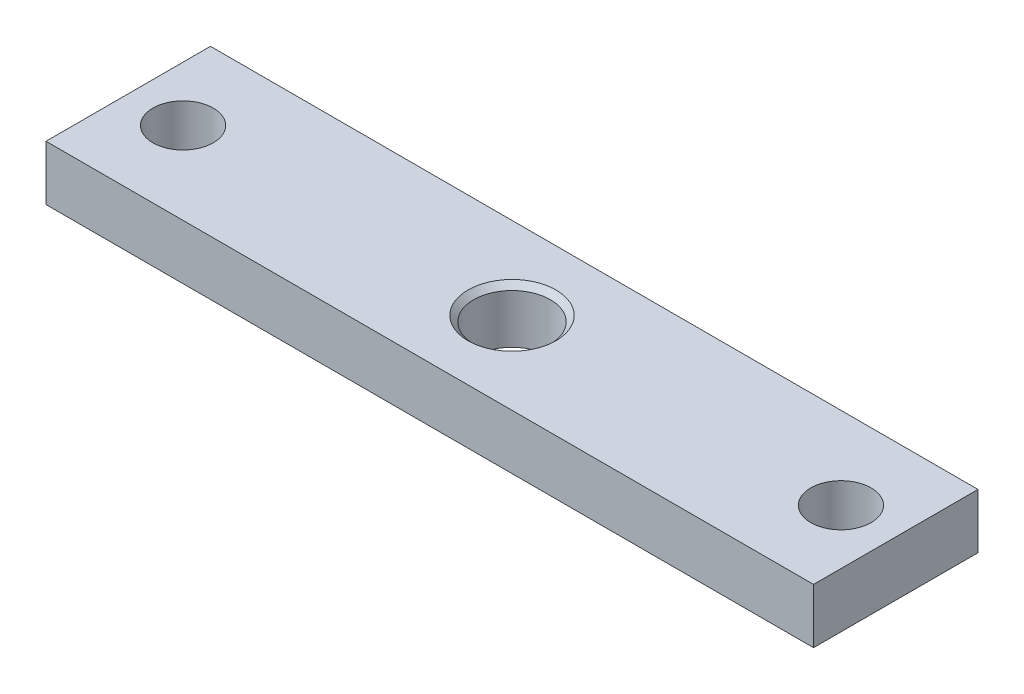
SolidWorks part; units mm, degrees
ref_plane "Front Plane" through (0, 0, 0) normal (0, 0, 1) x (1, 0, 0)
ref_plane "Top Plane" through (0, 0, 0) normal (0, 1, 0) x (1, 0, 0)
ref_plane "Right Plane" through (0, 0, 0) normal (1, 0, 0) x (0, 0, -1)
sketch "Sketch4" plane through (0, 0, 0) normal (0, 1, 0) x (1, 0, 0)
  line L1 (-70, 15) -> (70, 15)
  line L2 (-70, 15) -> (-70, -15)
  line L3 (-70, -15) -> (70, -15)
  line L4 (70, 15) -> (70, -15)
  line L5 (-70, 15) -> (70, -15) construction
  line L6 (-70, -15) -> (70, 15) construction
  point P0 (0, 0)
  dimension "D1" = 140
  dimension "D2" = 30
extrude "Boss-Extrude2" add sketch "Sketch4" along normal mid plane 10
sketch "Sketch5" plane through (0, 5, 0) normal (0, 1, 0) x (1, 0, 0)
  line L0 (-5.5, 0) -> (5.5, 0) construction
  circle A0 centre (-60, 0) radius 5.5
  circle A1 centre (60, 0) radius 5.5
  dimension "D1" = 11
  dimension "D2" = 60
  dimension "D3" = 120
extrude "Cut-Extrude1" cut sketch "Sketch5" against normal blind 63
sketch "Sketch6" plane through (0, 5, 0) normal (0, 1, 0) x (1, 0, 0)
  point P0 (0, 0)
hole_wizard "M16 Tapped Hole1" positions "3DSketch2" profile "Sketch8" tap size "M16" standard "ISO"
sketch3d "3DSketch2"
  point P0 (0, 5, 0)
sketch "Sketch8" plane through (0, 5, 0) normal (1, 0, 0) x (0, 0, 1)
  line L0 (0, 0) -> (0, 42.206)
  line L1 (0, 42.206) -> (7, 38)
  line L2 (7, 38) -> (7, 1.025)
  line L3 (7, 1.025) -> (8.025, 0)
  line L5 (8.025, 0) -> (0, 0)
  line L6 (-7, 1.025) -> (-8.025, 0) construction
  line L10 (0, 42.206) -> (-7, 38) construction
  line L11 (0, -6.35) -> (0, 107.95) construction
  dimension "Tap Drill Dia." = 14
  dimension "Tap Drill Depth" = 38
  dimension "Near C'Sink Dia." = 16.05
  dimension "Near C'Sink Angle" = 90
  dimension "Drill Angle" = 118
